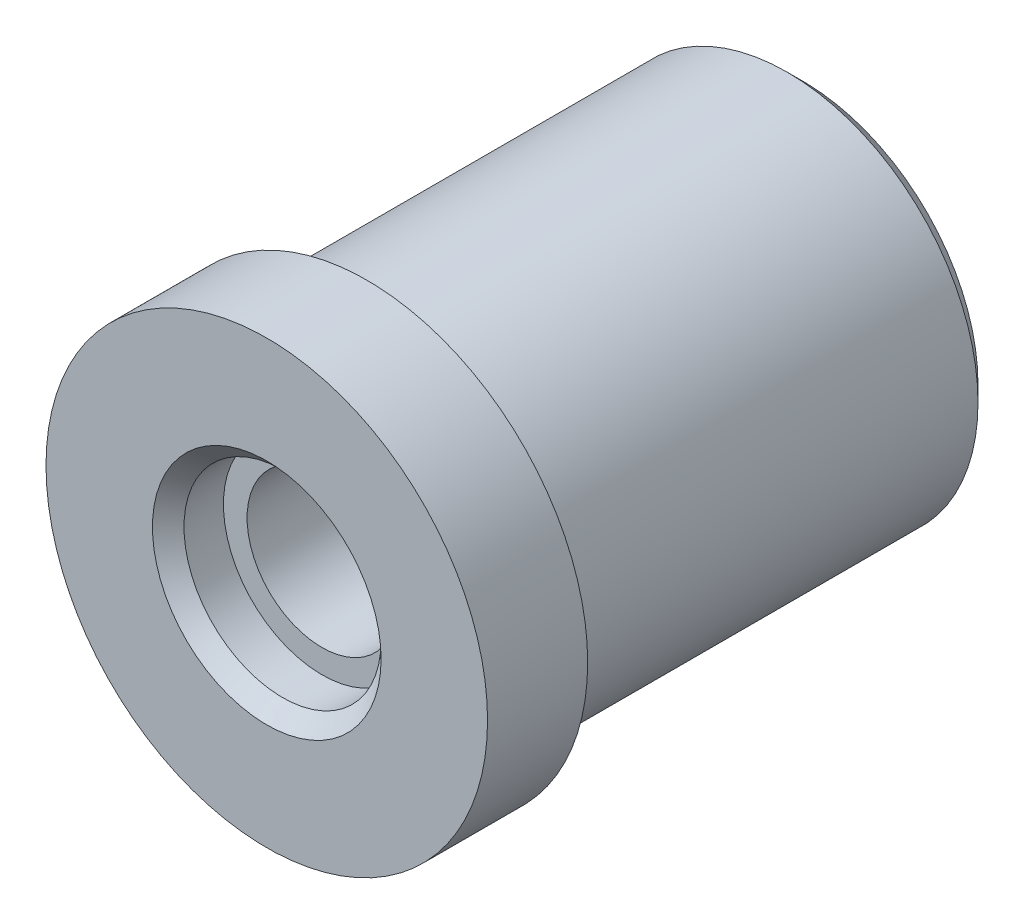
SolidWorks part; units mm, degrees
ref_plane "Front Plane" through (0, 0, 0) normal (0, 0, 1) x (1, 0, 0)
ref_plane "Top Plane" through (0, 0, 0) normal (0, 1, 0) x (1, 0, 0)
ref_plane "Right Plane" through (0, 0, 0) normal (1, 0, 0) x (0, 0, -1)
sketch "Sketch1" plane through (0, 0, 0) normal (0, 0, 1) x (1, 0, 0)
  circle A0 centre (0, 0) radius 12.1
  dimension "D1" = 24.2
extrude "Boss-Extrude1" add sketch "Sketch1" along normal mid plane 34
sketch "Sketch2" plane through (0, 0, 17) normal (0, 0, 1) x (1, 0, 0)
  circle A0 centre (0, 0) radius 4.75
  dimension "D1" = 9.5
extrude "Cut-Extrude1" cut sketch "Sketch2" against normal through all
sketch "Sketch3" plane through (0, 0, 17) normal (0, 0, 1) x (1, 0, 0)
  circle A0 centre (0, 0) radius 6.25
  dimension "D1" = 12.5
extrude "Cut-Extrude2" cut sketch "Sketch3" against normal blind 3.5
mirror "Mirror1" about plane through (0, 0, 0) normal (0, 0, 1) of "Cut-Extrude2"
sketch "Sketch4" plane through (0, 0, 17) normal (0, 0, 1) x (1, 0, 0)
  circle A0 centre (0, 0) radius 14
  circle M1 centre (0, 0) radius 6.25
  circle M2 centre (0, 0) radius 12.1
  dimension "D1" = 28
extrude "Boss-Extrude2" add sketch "Sketch4" against normal blind 6.35 contours A0 M2 | M2 M1
chamfer "Chamfer1" distance 1 angle 45 3 edges at (12.1, 0, -17) (6.25, 0, -17) (6.25, 0, 17)
